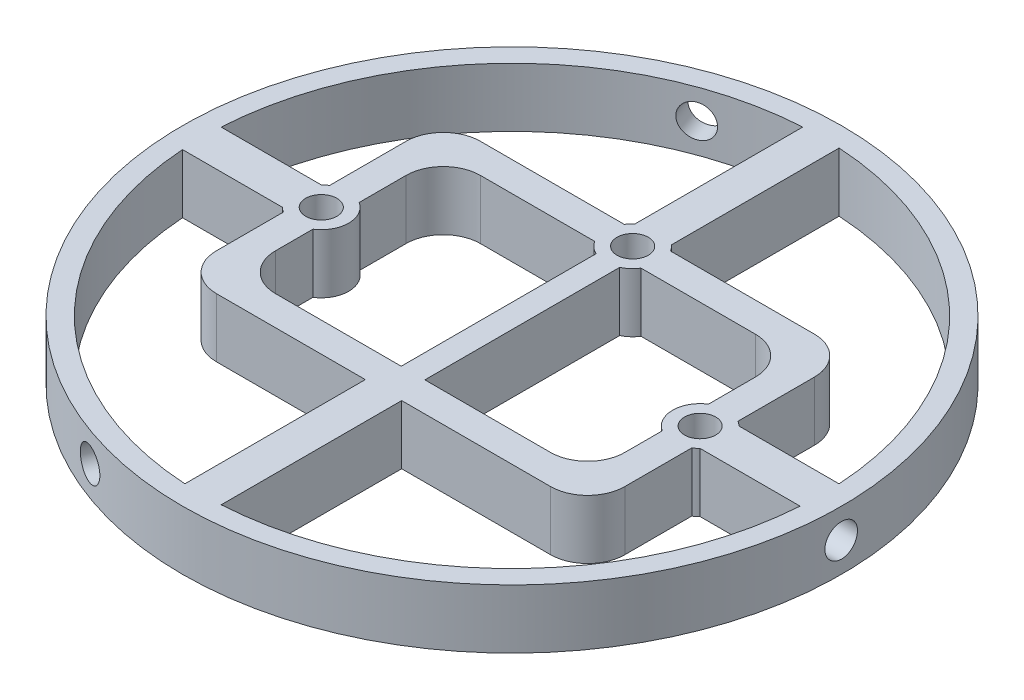
SolidWorks part; units mm, degrees
ref_plane "Front Plane" through (0, 0, 0) normal (0, 0, 1) x (1, 0, 0)
ref_plane "Top Plane" through (0, 0, 0) normal (0, 1, 0) x (1, 0, 0)
ref_plane "Right Plane" through (0, 0, 0) normal (1, 0, 0) x (0, 0, -1)
sketch "Sketch1" plane through (0, 0, 0) normal (0, 1, 0) x (1, 0, 0)
  line L0 (-23.2235, 4.0798) -> (-34.0464, 4.0798)
  line L1 (-23.2235, -4.3606) -> (-34.0116, -4.3606)
  line L2 (4.2178, 15.1224) -> (4.2178, 34.0296)
  line L3 (-4.2178, 15.1224) -> (-4.2178, 34.0296)
  line L4 (-4.2178, 8.7724) -> (-4.2178, -9.0532)
  line L5 (4.2178, -15.4032) -> (4.2178, -34.0296)
  line L6 (-4.2178, -15.4032) -> (-4.2178, -34.0296)
  line L10 (-16.8735, 4.0798) -> (-16.8735, 6.7724)
  line L11 (-14.8735, 8.7724) -> (-4.2178, 8.7724)
  line L17 (-4.2178, 15.1224) -> (-18.2235, 15.1224)
  line L18 (-23.2235, 10.1224) -> (-23.2235, 4.0798)
  line L20 (-23.2235, -10.4032) -> (-23.2235, -4.3606)
  line L21 (-4.2178, -15.4032) -> (-18.2235, -15.4032)
  line L24 (-14.8735, -9.0532) -> (-4.2178, -9.0532)
  line L25 (-16.8735, -4.3606) -> (-16.8735, -7.0532)
  line L27 (-16.8735, 4.0798) -> (-16.8735, -4.3606)
  line L28 (0, -41.2115) -> (0, 41.2115) construction
  line L30 (16.8735, -4.3606) -> (16.8735, -7.0532)
  line L31 (14.8735, -9.0532) -> (4.2178, -9.0532)
  line L34 (4.2178, -15.4032) -> (18.2235, -15.4032)
  line L35 (23.2235, -10.4032) -> (23.2235, -4.3606)
  line L38 (23.2235, 10.1224) -> (23.2235, 4.0798)
  line L39 (4.2178, 15.1224) -> (18.2235, 15.1224)
  line L42 (14.8735, 8.7724) -> (4.2178, 8.7724)
  line L43 (16.8735, 4.0798) -> (16.8735, 6.7724)
  line L45 (16.8735, 4.0798) -> (16.8735, -4.3606)
  line L46 (23.2235, 4.0798) -> (34.0464, 4.0798)
  line L47 (23.2235, -4.3606) -> (34.0116, -4.3606)
  line L48 (4.2178, -9.0532) -> (4.2178, 8.7724)
  circle A1 centre (0, 0) radius 34.29
  arc A2 (-23.2235, 10.1224) -> (-18.2235, 15.1224) centre (-18.2235, 10.1224) cw
  arc A3 (-16.8735, 6.7724) -> (-14.8735, 8.7724) centre (-14.8735, 6.7724) cw
  arc A4 (-23.2235, -10.4032) -> (-18.2235, -15.4032) centre (-18.2235, -10.4032) ccw
  arc A5 (-16.8735, -7.0532) -> (-14.8735, -9.0532) centre (-14.8735, -7.0532) ccw
  arc A6 (16.8735, -7.0532) -> (14.8735, -9.0532) centre (14.8735, -7.0532) cw
  arc A7 (23.2235, -10.4032) -> (18.2235, -15.4032) centre (18.2235, -10.4032) cw
  arc A8 (23.2235, 10.1224) -> (18.2235, 15.1224) centre (18.2235, 10.1224) ccw
  arc A9 (16.8735, 6.7724) -> (14.8735, 8.7724) centre (14.8735, 6.7724) ccw
  circle A10 centre (0, 0) radius 37.719
  dimension "D1" = 5
  dimension "D2" = 2
extrude "Boss-Extrude2" add sketch "Sketch1" along normal blind 6.35
sketch "Sketch2" plane through (0, 6.35, 0) normal (0, 1, 0) x (1, 0, 0)
  circle A3 centre (-20.366, -0.1404) radius 1.6802
  circle A4 centre (0, 12.9726) radius 1.6802
  circle A5 centre (20.366, -0.1404) radius 1.6802
extrude "Cut-Extrude1" cut sketch "Sketch2" against normal blind 6.35
sketch "Sketch3" plane through (0, 0, 0) normal (0, 0, 1) x (1, 0, 0)
  circle A0 centre (0, 3.175) radius 1.6802
sketch "Sketch4" plane through (0, 6.35, 0) normal (0, 1, 0) x (1, 0, 0)
  line L0 (0, 0) -> (-12.9007, 35.4443)
  line L1 (0, 0) -> (0, 136.0733)
  line L2 (0, -111.8498) -> (0, 111.8498) construction
  circle A1 centre (0, 0) radius 37.719 construction
  dimension "D1" = 20
ref_plane "Plane1" through (-12.9007, 6.35, -35.4443) normal (-0.342, 0, -0.9397) x (-0.9397, 0, 0.342)
sketch "Sketch5" plane through (-12.9007, 6.35, -35.4443) normal (-0.342, 0, -0.9397) x (-0.9397, 0, 0.342)
  circle A0 centre (0, -3.175) radius 1.6802
extrude "Cut-Extrude3" [suppressed] cut sketch "Sketch5" against normal blind 10
pattern_circular "CirPattern2" [suppressed] count 2 over 140
sketch "Sketch6" plane through (0, 0, 0) normal (1, 0, 0) x (0, 0, -1)
  circle A0 centre (0, 3.175) radius 1.6802
  circle A1 centre (0, 17.145) radius 1.6929
sketch "Sketch7" plane through (0, 6.35, 0) normal (0, 1, 0) x (1, 0, 0)
  line L0 (18.7785, 7.3851) -> (18.7785, 2.3463)
  line L1 (-2.9502, 14.5601) -> (-2.4867, 14.5601)
  line L2 (17.9535, 14.5601) -> (2.4867, 14.5601)
  line L3 (21.9535, 10.5601) -> (21.9535, 2.3463)
  line L4 (-1.27, 34.2665) -> (-1.27, 15.6354)
  line L5 (1.27, 34.2665) -> (1.27, 15.6354)
  line L6 (22.8527, 1.4471) -> (34.2595, 1.4471)
  line L7 (-2.9502, 11.3851) -> (-14.7785, 11.3851)
  line L8 (22.8527, -1.7279) -> (34.2464, -1.7279)
  line L9 (-34.2595, 1.4471) -> (-22.8527, 1.4471)
  line L10 (-18.7785, 7.3851) -> (-18.7785, 2.3463)
  line L11 (-2.9502, 11.3851) -> (-2.4867, 11.3851)
  line L12 (21.9535, -9.8157) -> (21.9535, -2.6271)
  line L13 (-2.9502, 14.5601) -> (-17.9535, 14.5601)
  line L14 (-21.9535, 10.5601) -> (-21.9535, 2.3463)
  line L15 (-34.2464, -1.7279) -> (-22.8527, -1.7279)
  line L16 (2.4867, 11.3851) -> (14.7785, 11.3851)
  line L17 (-1.27, 10.3097) -> (-1.27, -34.2665)
  line L18 (1.27, 10.3097) -> (1.27, -34.2665)
  line L20 (4.2178, -13.8157) -> (17.9535, -13.8157)
  line L21 (4.2178, -10.6407) -> (14.7785, -10.6407)
  line L22 (18.7785, -6.6407) -> (18.7785, -2.6271)
  line L23 (-18.7785, -2.6271) -> (-18.7785, -6.6407)
  line L24 (-14.7785, -10.6407) -> (4.2178, -10.6407)
  line L25 (-21.9535, -2.6271) -> (-21.9535, -9.8157)
  line L26 (-17.9535, -13.8157) -> (4.2178, -13.8157)
  arc A0 (-21.9535, -9.8157) -> (-17.9535, -13.8157) centre (-17.9535, -9.8157) ccw
  circle A1 centre (0, 12.9726) radius 2.9502
  circle A2 centre (0, 0) radius 34.29
  circle A3 centre (-20.366, -0.1404) radius 2.9502
  circle A4 centre (20.366, -0.1404) radius 2.9502
  arc A5 (-14.7785, -10.6407) -> (-18.7785, -6.6407) centre (-14.7785, -6.6407) cw
  arc A6 (17.9535, -13.8157) -> (21.9535, -9.8157) centre (17.9535, -9.8157) ccw
  arc A7 (14.7785, -10.6407) -> (18.7785, -6.6407) centre (14.7785, -6.6407) ccw
  arc A8 (18.7785, 7.3851) -> (14.7785, 11.3851) centre (14.7785, 7.3851) ccw
  arc A9 (21.9535, 10.5601) -> (17.9535, 14.5601) centre (17.9535, 10.5601) ccw
  arc A10 (-18.7785, 7.3851) -> (-14.7785, 11.3851) centre (-14.7785, 7.3851) cw
  arc A11 (-21.9535, 10.5601) -> (-17.9535, 14.5601) centre (-17.9535, 10.5601) cw
  line M12 (-4.2178, 34.0296) -> (-4.2178, 15.1224)
  line M13 (-4.2178, 15.1224) -> (-18.2235, 15.1224)
  arc M14 (-18.2235, 15.1224) -> (-23.2235, 10.1224) centre (-18.2235, 10.1224) ccw
  line M15 (-23.2235, 10.1224) -> (-23.2235, 4.0798)
  line M16 (-23.2235, 4.0798) -> (-34.0464, 4.0798)
  line M18 (-34.0116, -4.3606) -> (-23.2235, -4.3606)
  line M19 (-23.2235, -4.3606) -> (-23.2235, -10.4032)
  arc M20 (-23.2235, -10.4032) -> (-18.2235, -15.4032) centre (-18.2235, -10.4032) ccw
  line M21 (-18.2235, -15.4032) -> (-4.2178, -15.4032)
  line M22 (-4.2178, -15.4032) -> (-4.2178, -34.0296)
  line M24 (4.2178, -34.0296) -> (4.2178, -15.4032)
  line M25 (4.2178, -15.4032) -> (18.2235, -15.4032)
  arc M26 (18.2235, -15.4032) -> (23.2235, -10.4032) centre (18.2235, -10.4032) ccw
  line M27 (23.2235, -10.4032) -> (23.2235, -4.3606)
  line M28 (23.2235, -4.3606) -> (34.0116, -4.3606)
  arc M29 (14.8735, 8.7724) -> (16.8735, 6.7724) centre (14.8735, 6.7724) cw
  line M30 (16.8735, 6.7724) -> (16.8735, -7.0532)
  arc M31 (16.8735, -7.0532) -> (14.8735, -9.0532) centre (14.8735, -7.0532) cw
  line M32 (14.8735, -9.0532) -> (4.2178, -9.0532)
  line M33 (4.2178, -9.0532) -> (4.2178, 8.7724)
  line M34 (4.2178, 8.7724) -> (14.8735, 8.7724)
  arc M35 (-14.8735, -9.0532) -> (-16.8735, -7.0532) centre (-14.8735, -7.0532) cw
  line M36 (-16.8735, -7.0532) -> (-16.8735, 6.7724)
  arc M37 (-16.8735, 6.7724) -> (-14.8735, 8.7724) centre (-14.8735, 6.7724) cw
  line M38 (-14.8735, 8.7724) -> (-4.2178, 8.7724)
  line M39 (-4.2178, 8.7724) -> (-4.2178, -9.0532)
  line M40 (-4.2178, -9.0532) -> (-14.8735, -9.0532)
  line M41 (23.2235, 4.0798) -> (23.2235, 10.1224)
  arc M42 (23.2235, 10.1224) -> (18.2235, 15.1224) centre (18.2235, 10.1224) ccw
  line M43 (18.2235, 15.1224) -> (4.2178, 15.1224)
  line M44 (4.2178, 15.1224) -> (4.2178, 34.0296)
  line M46 (34.0464, 4.0798) -> (23.2235, 4.0798)
  dimension "D1" = 4
  dimension "D2" = 4
  dimension "D3" = 4
extrude "Cut-Extrude5" cut sketch "Sketch7" against normal blind 10 contours L14 A11 L13 L1 A1 L4 A2 L9 A3 M12 M13 M14 M15 M16 | A9 L3 A4 L6 A2 L5 A1 L2 M46 M41 M42 M43 M44 | A6 L20 L26 L18 A2 L8 A4 L12 M24 M25 M26 M27 M28 | A3 L15 A2 L17 L26 A0 L25 M18 M19 M20 M21 M22 | A10 L10 A3 L23 A5 L24 L17 A1 L11 L7 M40 M35 M36 M37 M38 M39 | L0 A8 L16 A1 L18 L24 L21 A7 L22 A4 M34 M29 M30 M31 M32 M33
sketch "Sketch8" plane through (0, 0, 0) normal (0, -1, 0) x (1, 0, 0)
  line L1 (-26.4656, 3.3154) -> (-37.318, 3.3154)
  line L3 (-26.4656, 1.7279) -> (-26.4656, 3.3154)
  line L4 (-34.2464, 1.7279) -> (-22.8527, 1.7279) construction
  line L5 (-26.4656, 3.3154) -> (-26.4656, -3.0346)
  line L6 (-26.4656, -3.0346) -> (-37.3419, -3.0346)
  circle A0 centre (0, 0) radius 37.465
  circle A1 centre (0, 0) radius 34.29
extrude "Boss-Extrude3" add sketch "Sketch8" against normal blind 6.35 contours A1 L1 A0 L6
sketch "Sketch10" plane through (0, 6.35, 0) normal (0, 1, 0) x (1, 0, 0)
  line L0 (1.9538, 15.1831) -> (1.9538, 34.2343)
  line L1 (-1.9538, 15.1831) -> (-1.9538, 34.2343)
  line L2 (1.9538, -13.8157) -> (1.9538, -34.2343)
  line L3 (1.27, -13.8157) -> (17.9535, -13.8157) construction
  line L4 (-1.9538, -13.8157) -> (-1.9538, -34.2343)
  line L5 (-17.9535, -13.8157) -> (-1.27, -13.8157) construction
  line L6 (-1.9538, 15.1831) -> (1.9538, 15.1831)
  line L7 (-1.9538, -13.8157) -> (1.9538, -13.8157)
  line L8 (-22.4521, 1.9457) -> (-30.0721, 1.9457)
  line L9 (-30.0721, 1.9457) -> (-34.2348, 1.9457)
  line L10 (-30.0721, -2.2265) -> (-34.2176, -2.2265)
  line L12 (-22.4521, -2.2265) -> (-30.0721, -2.2265)
  line L15 (0, -13.8533) -> (0, 13.8533) construction
  line L16 (22.4521, -2.2265) -> (30.0721, -2.2265)
  line L18 (22.4521, 1.9457) -> (30.0721, 1.9457)
  line L22 (-22.4521, -2.2265) -> (-22.4521, 1.9457)
  line L23 (22.4521, 1.9457) -> (22.4521, -2.2265)
  line L24 (30.0721, -2.2265) -> (34.2176, -2.2265)
  line L25 (30.0721, 1.9457) -> (34.2348, 1.9457)
  arc A0 (2.4867, 14.5601) -> (1.27, 15.6354) centre (0, 12.9726) ccw construction
  circle A1 centre (0, 0) radius 34.29 construction
  arc A2 (-1.27, 15.6354) -> (-2.4867, 14.5601) centre (0, 12.9726) ccw construction
  circle A3 centre (0, 0) radius 34.29 construction
  circle A4 centre (0, 0) radius 34.29 construction
  circle A5 centre (0, 0) radius 34.29 construction
  circle A6 centre (0, 0) radius 34.29
  arc A7 (-21.9535, 2.3463) -> (-22.8527, 1.4471) centre (-20.366, -0.1404) ccw construction
  arc A8 (-22.8527, -1.7279) -> (-21.9535, -2.6271) centre (-20.366, -0.1404) ccw construction
extrude "Boss-Extrude4" add sketch "Sketch10" against normal up to surface (6.35 mm away) up to face at (-18.3861, 0, 12.155)
pattern_circular "CirPattern3" count 2 every 70 of "Boss-Extrude3"
sketch "Sketch11" plane through (0, 6.35, 0) normal (0, 1, 0) x (1, 0, 0)
  line L0 (30.0721, 3.0346) -> (34.1555, 3.0346)
  line L1 (30.0721, -3.2953) -> (34.1313, -3.2953)
  line L2 (34.1313, -3.2953) -> (37.3198, -3.2953)
  line L3 (34.1555, 3.0346) -> (37.3419, 3.0346)
  circle A0 centre (0, 0) radius 30.2521
  circle A1 centre (0, 0) radius 34.29
  circle A2 centre (0, 0) radius 37.465 construction
  circle A3 centre (0, 0) radius 37.465
sketch "Sketch13" plane through (-12.9007, 6.35, -35.4443) normal (-0.342, 0, -0.9397) x (-0.9397, 0, 0.342)
  circle A0 centre (0, -3.175) radius 1.7526
extrude "Cut-Extrude7" cut sketch "Sketch13" against normal blind 6.35
pattern_circular "CirPattern4" count 2 over 140 of "Cut-Extrude7"
sketch "Sketch14" plane through (0, 6.35, 0) normal (0, 1, 0) x (1, 0, 0)
  line L0 (-34.2348, 1.9457) -> (-34.8869, 1.9457)
  line L1 (-34.2176, -2.2265) -> (-34.8701, -2.2265)
  line L2 (-1.9538, -34.2343) -> (-1.9538, -34.8864)
  line L3 (1.9538, -34.2343) -> (1.9538, -34.8864)
  line L4 (34.2348, 1.9457) -> (34.8869, 1.9457)
  line L5 (34.2176, -2.2265) -> (34.8701, -2.2265)
  line L6 (1.9538, 34.2343) -> (1.9538, 34.8864)
  line L7 (-1.9538, 34.2343) -> (-1.9538, 34.8864)
  circle A0 centre (0, 0) radius 37.719
  circle A2 centre (0, 0) radius 34.9411
  circle A3 centre (0, 0) radius 34.29
extrude "Cut-Extrude8" cut sketch "Sketch14" against normal blind 10.414 contours A3 L7 A2 L0 | A3 L4 A2 L6 | A3 L3 A2 L5 | A3 L1 A2 L2
sketch "Sketch15" plane through (0, 6.35, 0) normal (0, 1, 0) x (1, 0, 0)
  circle A0 centre (0, 0) radius 34.9411
  circle A1 centre (0, 0) radius 37.719
sketch "Sketch16" plane through (0, 0, 0) normal (1, 0, 0) x (0, 0, -1)
  circle A0 centre (0, 3.175) radius 1.7526
extrude "Cut-Extrude9" cut sketch "Sketch16" against normal blind 21.59 from offset 50.8
sketch "Sketch17" plane through (0, 6.35, 0) normal (0, 1, 0) x (1, 0, 0)
  circle A1 centre (0, 0) radius 58.3804
  circle A2 centre (0, 0) radius 35.433
extrude "Cut-Extrude10" cut sketch "Sketch17" against normal blind 18.796
sketch "Sketch18" plane through (0, 6.35, 0) normal (0, 1, 0) x (1, 0, 0)
  circle A0 centre (0, 0) radius 33.274
  circle A2 centre (0, 0) radius 34.9411
extrude "Boss-Extrude5" add sketch "Sketch18" against normal up to surface (6.35 mm away) up to face at (-18.5897, 0, 12.3575)
sketch "Sketch19" plane through (0, 0, 0) normal (1, 0, 0) x (0, 0, -1)
  circle A0 centre (0, 3.175) radius 1.7526
extrude "Cut-Extrude11" cut sketch "Sketch19" against normal blind 22.86 from offset 50.8
pattern_circular "CirPattern6" count 2 every 110 of "Cut-Extrude11"
pattern_circular "CirPattern7" count 2 over 360 of "Cut-Extrude11"
